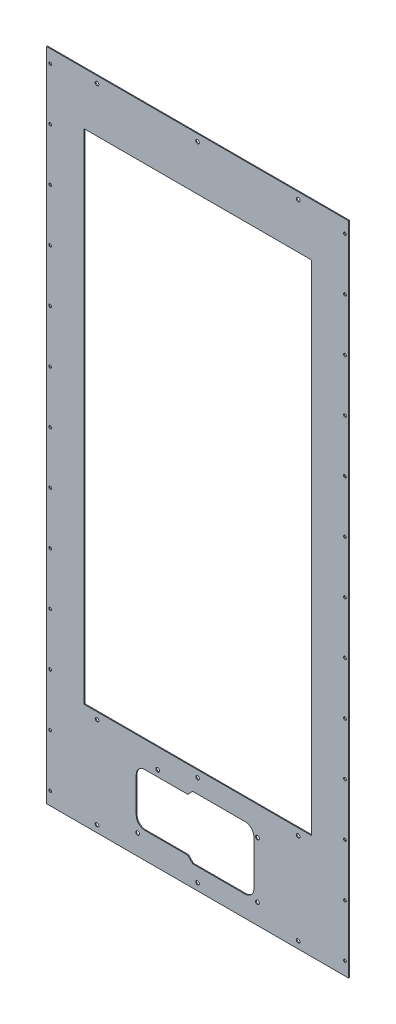
SolidWorks part; units mm, degrees
ref_plane "Front Plane" through (0, 0, 0) normal (0, 0, 1) x (1, 0, 0)
ref_plane "Top Plane" through (0, 0, 0) normal (0, 1, 0) x (1, 0, 0)
ref_plane "Right Plane" through (0, 0, 0) normal (1, 0, 0) x (0, 0, -1)
sketch "Sketch1" plane through (0, 0, 0) normal (0, 0, 1) x (1, 0, 0)
  line L0 (-673.5642, -82.6035) -> (-328.5642, -82.6035)
  line L1 (-328.5642, -82.6035) -> (-328.5642, -832.6035)
  line L4 (-673.5642, -82.6035) -> (-673.5642, -832.6035)
  line L5 (-673.5642, -832.6035) -> (-328.5642, -832.6035)
  line L6 (-371.0198, -712.6035) -> (-631.0198, -712.6035)
  line L7 (-631.0198, -712.6035) -> (-631.0198, -142.6035)
  line L8 (-631.0198, -142.6035) -> (-371.0198, -142.6035)
  line L9 (-371.0198, -142.6035) -> (-371.0198, -712.6035)
  line L11 (-436.7042, -798.5324) -> (-436.7042, -746.8324)
  line L13 (-446.7042, -736.8324) -> (-506.7042, -736.8324)
  line L32 (-506.7042, -808.5324) -> (-512.2704, -802.7824)
  line L48 (-512.2704, -742.5824) -> (-506.7042, -736.8324)
  line L49 (-512.2704, -742.5824) -> (-561.2042, -742.5824)
  line L50 (-571.2042, -752.5824) -> (-571.2042, -792.7824)
  line L51 (-561.2042, -802.7824) -> (-512.2704, -802.7824)
  line L52 (-506.7042, -808.5324) -> (-446.7042, -808.5324)
  circle A28 centre (-432.5642, -809.5824) radius 2.2
  circle A29 centre (-432.5642, -745.5824) radius 2.2
  circle A30 centre (-546.5642, -735.5824) radius 2.2
  circle A31 centre (-569.5642, -809.5824) radius 2.2
  circle A32 centre (-501.0642, -90.6035) radius 2.1
  circle A33 centre (-616.0642, -90.6035) radius 2.1
  circle A34 centre (-386.0642, -90.6035) radius 2.1
  circle A35 centre (-616.0198, -720.6035) radius 2.1
  circle A36 centre (-501.0198, -720.6035) radius 2.1
  circle A37 centre (-386.0198, -720.6035) radius 2.1
  circle A38 centre (-386.0642, -824.6035) radius 2.1
  circle A39 centre (-501.0642, -824.6035) radius 2.1
  circle A40 centre (-616.0642, -824.6035) radius 2.1
  arc A41 (-446.7042, -736.8324) -> (-436.7042, -746.8324) centre (-446.7042, -746.8324) cw
  arc A42 (-446.7042, -808.5324) -> (-436.7042, -798.5324) centre (-446.7042, -798.5324) ccw
  arc A43 (-561.2042, -742.5824) -> (-571.2042, -752.5824) centre (-561.2042, -752.5824) ccw
  arc A44 (-571.2042, -792.7824) -> (-561.2042, -802.7824) centre (-561.2042, -792.7824) ccw
extrude "Boss-Extrude1" add sketch "Sketch1" along normal blind 1
sketch "Sketch2" plane through (0, 0, 1) normal (0, 0, 1) x (1, 0, 0)
  line L0 (-673.5642, -82.6035) -> (-665.7042, -82.6035)
  line L1 (-673.5642, -82.6035) -> (-328.5642, -82.6035) construction
  line L5 (-665.7042, -97.6035) -> (-669.6342, -97.6035)
  circle A0 centre (-669.6342, -97.6035) radius 1.6
  circle A1 centre (-669.6342, -817.6035) radius 1.6
  circle A2 centre (-669.6342, -757.6035) radius 1.6
  circle A3 centre (-669.6342, -697.6035) radius 1.6
  circle A4 centre (-669.6342, -637.6035) radius 1.6
  circle A5 centre (-669.6342, -577.6035) radius 1.6
  circle A6 centre (-669.6342, -517.6035) radius 1.6
  circle A7 centre (-669.6342, -457.6035) radius 1.6
  circle A8 centre (-669.6342, -397.6035) radius 1.6
  circle A9 centre (-669.6342, -337.6035) radius 1.6
  circle A10 centre (-669.6342, -277.6035) radius 1.6
  circle A11 centre (-669.6342, -217.6035) radius 1.6
  circle A12 centre (-669.6342, -157.6035) radius 1.6
extrude "Cut-Extrude1" cut sketch "Sketch2" against normal blind 1 contours A1 | A2 | A3 | A4 | A5 | A6 | A7 | A8 | A9 | A10 | A11 | A12 | A0
sketch "Sketch3" plane through (0, 0, 1) normal (0, 0, 1) x (1, 0, 0)
  circle A0 centre (-332.5142, -97.6035) radius 1.6
  circle A1 centre (-332.5142, -817.6035) radius 1.6
  circle A2 centre (-332.5142, -757.6035) radius 1.6
  circle A3 centre (-332.5142, -697.6035) radius 1.6
  circle A4 centre (-332.5142, -637.6035) radius 1.6
  circle A5 centre (-332.5142, -577.6035) radius 1.6
  circle A6 centre (-332.5142, -517.6035) radius 1.6
  circle A7 centre (-332.5142, -457.6035) radius 1.6
  circle A8 centre (-332.5142, -397.6035) radius 1.6
  circle A9 centre (-332.5142, -337.6035) radius 1.6
  circle A10 centre (-332.5142, -277.6035) radius 1.6
  circle A11 centre (-332.5142, -217.6035) radius 1.6
  circle A12 centre (-332.5142, -157.6035) radius 1.6
extrude "Cut-Extrude2" cut sketch "Sketch3" against normal blind 1
